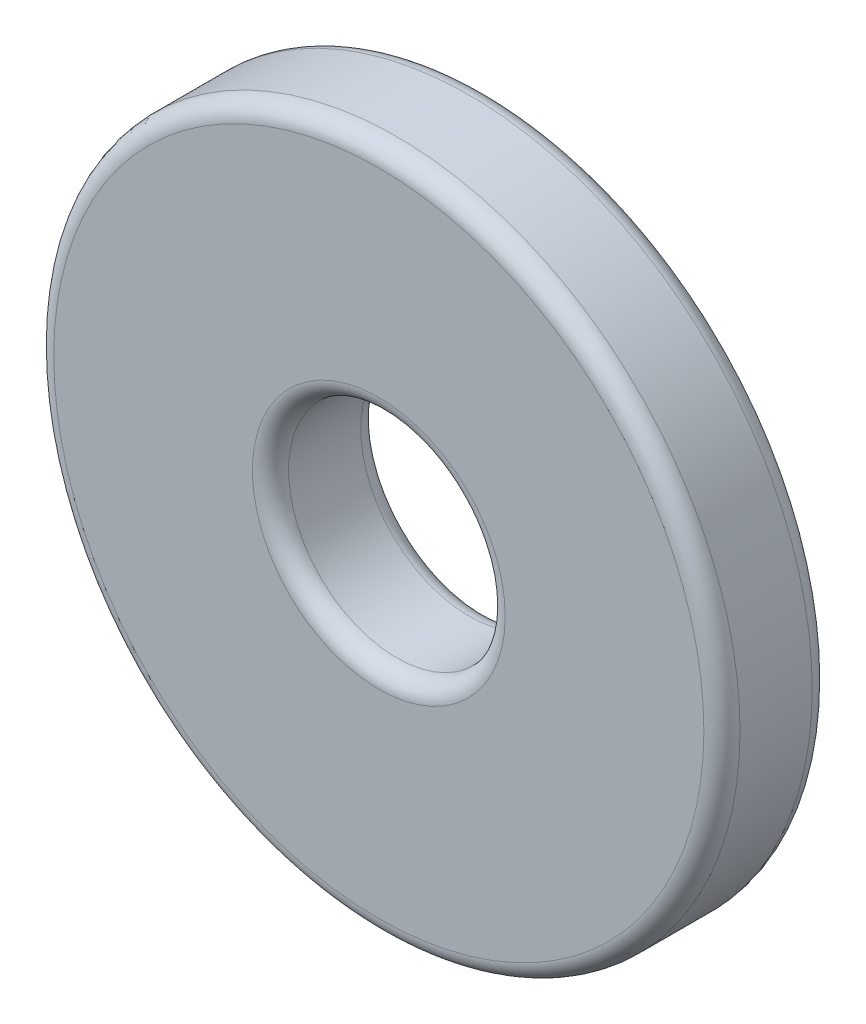
SolidWorks part; units mm, degrees
ref_plane "Plano frontal" through (0, 0, 0) normal (0, 0, 1) x (1, 0, 0)
ref_plane "Plano superior" through (0, 0, 0) normal (0, 1, 0) x (1, 0, 0)
ref_plane "Plano direito" through (0, 0, 0) normal (1, 0, 0) x (0, 0, -1)
sketch "Esboço1" plane through (0, 0, 0) normal (0, 0, 1) x (1, 0, 0)
  circle A0 centre (0, 0) radius 9.5
  circle A1 centre (0, 0) radius 3
extrude "Ressalto-extrusão1" add sketch "Esboço1" along normal mid plane 3
fillet "Filete1" radius 0.5 1 edges at (9.5, 0, 1.5)
fillet "Filete2" radius 0.5 1 edges at (9.5, 0, -1.5)
fillet "Filete3" radius 0.5 2 edges at (3, 0, -1.5) (3, 0, 1.5)
